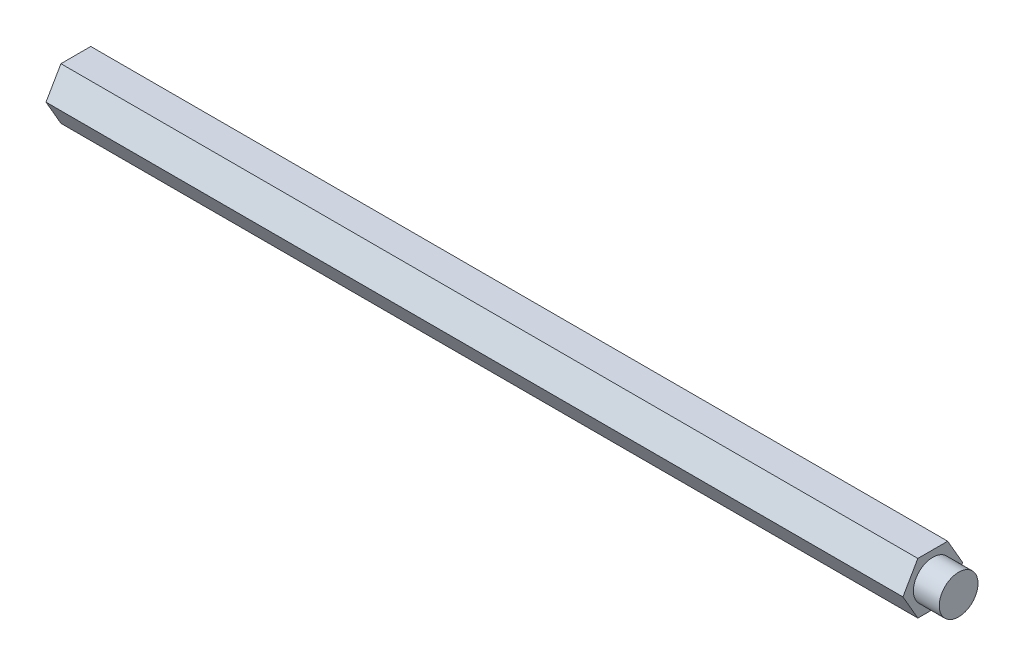
SolidWorks part; units mm, degrees
ref_plane "Alzado" through (0, 0, 0) normal (0, 0, 1) x (1, 0, 0)
ref_plane "Planta" through (0, 0, 0) normal (0, 1, 0) x (1, 0, 0)
ref_plane "Vista lateral" through (0, 0, 0) normal (1, 0, 0) x (0, 0, -1)
sketch "Croquis1" plane through (0, 0, 0) normal (1, 0, 0) x (0, 0, -1)
  line L1 (7.3323, 0) -> (3.6662, 6.35)
  line L2 (3.6662, 6.35) -> (-3.6662, 6.35)
  line L3 (-3.6662, 6.35) -> (-7.3323, 0)
  line L4 (-7.3323, 0) -> (-3.6662, -6.35)
  line L5 (-3.6662, -6.35) -> (3.6662, -6.35)
  line L6 (3.6662, -6.35) -> (7.3323, 0)
  circle A0 centre (0, 0) radius 6.35 construction
  dimension "D1" = 12.7
extrude "Saliente-Extruir1" add sketch "Croquis1" along normal blind 210.53
sketch "Croquis2" plane through (210.53, 0, 0) normal (1, 0, 0) x (0, 0, -1)
  circle A0 centre (0, 0) radius 4.7625
  dimension "D1" = 9.525
extrude "Saliente-Extruir2" add sketch "Croquis2" along normal blind 6.35
